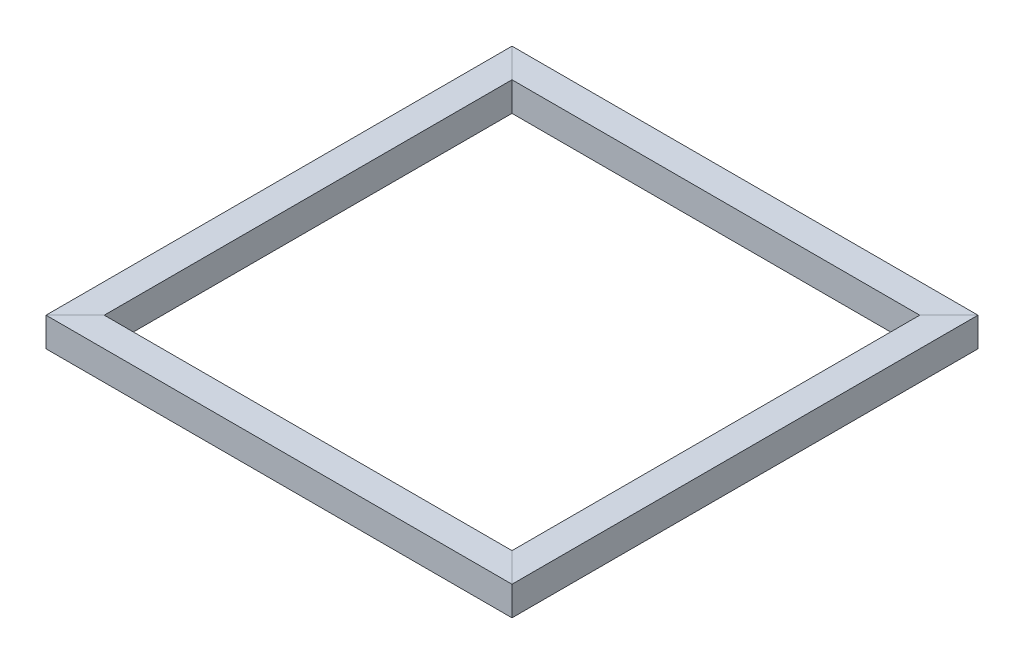
SolidWorks part; units mm, degrees
ref_plane "Alzado" through (0, 0, 0) normal (0, 0, 1) x (1, 0, 0)
ref_plane "Planta" through (0, 0, 0) normal (0, 1, 0) x (1, 0, 0)
ref_plane "Vista lateral" through (0, 0, 0) normal (1, 0, 0) x (0, 0, -1)
sketch "Croquis1" plane through (0, 0, 0) normal (0, 1, 0) x (1, 0, 0)
  line L1 (-150, 150) -> (150, 150)
  line L2 (-150, 150) -> (-150, -150)
  line L3 (-150, -150) -> (150, -150)
  line L4 (150, 150) -> (150, -150)
  line L5 (-150, 150) -> (150, -150) construction
  line L6 (-150, -150) -> (150, 150) construction
  point P0 (0, 0)
  point P6 (0, 0)
  dimension "D1" = 300
  dimension "D2" = 300
other "Tubo cuadrado 20 X 20 X 2(2)"
ref_plane "Plano2" through (-150, 0, -150) normal (0, 0, 1) x (1, 0, 0)
sketch "Sketch1" plane through (-150, 0, -150) normal (0, 0, 1) x (1, 0, 0)
  line L2 (10, 10) -> (-10, 10)
  line L3 (10, 10) -> (10, -10)
  line L4 (10, -10) -> (-10, -10)
  line L5 (-10, 10) -> (-10, -10)
  line L6 (10, 10) -> (-10, -10) construction
  line L7 (10, -10) -> (-10, 10) construction
  line L8 (-8, 8) -> (8, 8)
  line L9 (-8, 8) -> (-8, -8)
  line L10 (-8, -8) -> (8, -8)
  line L11 (8, 8) -> (8, -8)
  line L12 (-8, 8) -> (8, -8) construction
  line L13 (-8, -8) -> (8, 8) construction
  point P0 (0, 0)
  point P5 (0, 0)
  dimension "D1" = 20
  dimension "D2" = 20
  dimension "D3" = 2
